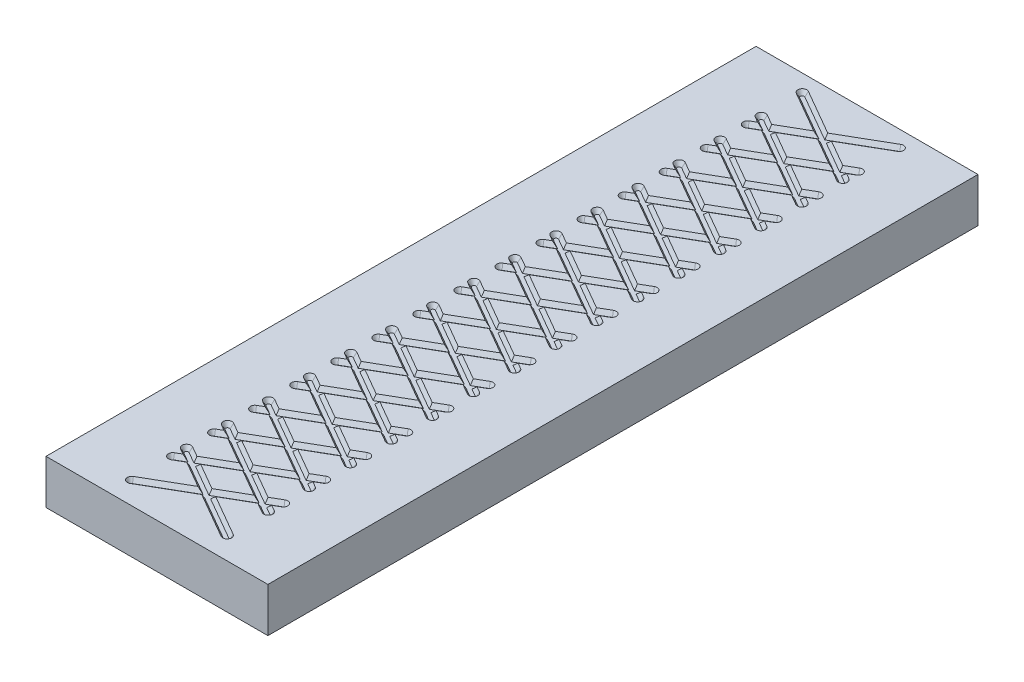
SolidWorks part; units mm, degrees
ref_plane "Front Plane" through (0, 0, 0) normal (0, 0, 1) x (1, 0, 0)
ref_plane "Top Plane" through (0, 0, 0) normal (0, 1, 0) x (1, 0, 0)
ref_plane "Right Plane" through (0, 0, 0) normal (1, 0, 0) x (0, 0, -1)
sketch "Sketch1" plane through (0, 0, 0) normal (0, 0, 1) x (1, 0, 0)
  line L1 (0, 0) -> (50, 0)
  line L2 (0, 0) -> (0, 10)
  line L3 (0, 10) -> (50, 10)
  line L4 (50, 0) -> (50, 10)
  dimension "D1" = 10
  dimension "D2" = 50
extrude "Boss-Extrude1" add sketch "Sketch1" against normal blind 160
sketch "Sketch2" plane through (0, 10, 0) normal (0, 1, 0) x (1, 0, 0)
  line L0 (14.2772, 143.8) -> (35.9279, 156.3) construction
  line L1 (13.7772, 144.666) -> (23, 149.9908)
  line L2 (14.7772, 142.934) -> (25, 148.8361)
  line L3 (25, 160) -> (25, 0) construction
  line L6 (50, 160) -> (0, 160) construction
  line L7 (50, 0) -> (0, 0) construction
  line L8 (35.8253, 143.7408) -> (14.1747, 156.2408) construction
  line L9 (36.3253, 144.6068) -> (27, 149.9908)
  line L10 (35.3253, 142.8748) -> (25, 148.8361)
  line L101 (25, 151.1455) -> (14.6747, 157.1068)
  line L102 (25, 151.1455) -> (35.4279, 157.166)
  line L103 (27, 149.9908) -> (36.4279, 155.434)
  line L104 (23, 149.9908) -> (13.6747, 155.3748)
  arc A0 (13.7772, 144.666) -> (14.7772, 142.934) centre (14.2772, 143.8) ccw
  arc A1 (36.4279, 155.434) -> (35.4279, 157.166) centre (35.9279, 156.3) ccw
  arc A4 (36.3253, 144.6068) -> (35.3253, 142.8748) centre (35.8253, 143.7408) cw
  arc A5 (13.6747, 155.3748) -> (14.6747, 157.1068) centre (14.1747, 156.2408) cw
  point P2 (25, 149.9908)
  point P10 (25, 160)
  point P27 (25, 149.9908)
  dimension "D1" = 2
  dimension "D2" = 25
  dimension "D3" = 30
  dimension "D4" = 3.7
  dimension "D6" = 25
  dimension "D5" = 30
extrude "Cut-Extrude2" cut sketch "Sketch2" against normal blind 1 draft 30 contours L1 L104 A5 L101 L102 A1 L103 L9 A4 L10 L2 A0
pattern_linear "LPattern1" count 16 spacing 9.25 along (0, 0, 1) of "Cut-Extrude2"
ref_plane "Plane1" through (0, 0, -80) normal (0, 0, 1) x (1, 0, 0)
ref_plane "Plane2" through (25, 0, 0) normal (1, 0, 0) x (0, 0, -1)
sketch "Sketch4" plane through (0, 0, 0) normal (0, -1, 0) x (1, 0, 0)
  line L8 (27.45, -48.7) -> (27.45, -38.8)
  line L9 (27.45, -38.8) -> (22.55, -38.8)
  line L10 (22.55, -38.8) -> (22.55, -48.7)
  line L11 (22.55, -48.7) -> (27.45, -48.7)
  line L12 (27.45, -48.7) -> (27.45, -38.8)
  line L13 (27.45, -38.8) -> (22.55, -38.8)
  line L14 (22.55, -38.8) -> (22.55, -48.7)
  line L15 (22.55, -48.7) -> (27.45, -48.7)
  dimension "D1" = 0.05
extrude "Cut-Extrude3" cut sketch "Sketch4" against normal blind 3.05 contours L12 L13 L14 L15
fillet "Fillet1" radius 1 8 edges at (25, 3.05, -38.8) (27.45, 3.05, -43.75) (25, 3.05, -48.7) (22.55, 3.05, -43.75) (25, 0, -48.7) (22.55, 0, -43.75) (25, 0, -38.8) (27.45, 0, -43.75)
mirror "Mirror1" about plane through (0, 0, -80) normal (0, 0, 1) of "Cut-Extrude3"
ref_plane "Plane3" through (0, 0, 0) normal (0, -1, 0) x (-1, 0, 0)
ref_plane "Plane4" through (0, 0, -43.75) normal (0, 0, -1) x (-1, 0, 0)
ref_plane "Plane5" through (0, 0, -116.25) normal (0, 0, -1) x (-1, 0, 0)
equation "\"tol\"=0.05"
equation "\"D1@Sketch4\"=\"tol\""
equation "\"D1@Cut-Extrude3\"=3mm +\"tol\""
